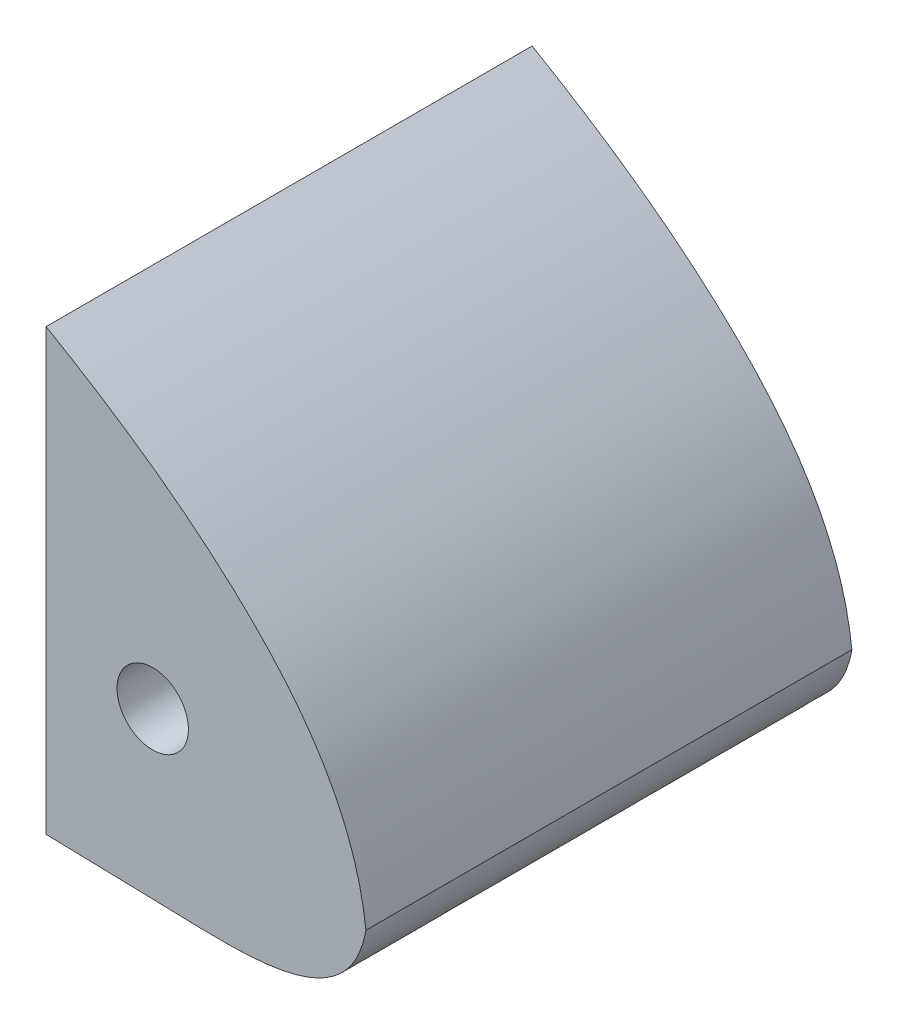
SolidWorks part; units mm, degrees
ref_plane "Front Plane" through (0, 0, 0) normal (0, 0, 1) x (1, 0, 0)
ref_plane "Top Plane" through (0, 0, 0) normal (0, 1, 0) x (1, 0, 0)
ref_plane "Right Plane" through (0, 0, 0) normal (1, 0, 0) x (0, 0, -1)
sketch "Sketch1" plane through (0, 0, 0) normal (0, 0, 1) x (1, 0, 0)
  line L0 (-66.007, 14.9523) -> (-66.007, -5.6347)
  circle A0 centre (63.517, -7.2283) radius 2.127
  circle A1 centre (-25.383, 13.0917) radius 2.127
  spline S0 degree 3 poles (76.217, -12.3083) (75.607, -6.7666) (69.7043, 1.1384) (56.4222, 10.2644) (36.9761, 19.3708) (8.7417, 24.8154) (-27.4552, 23.5667) (-52.3876, 18.1036) (-66.007, 14.9523) knots 0 0 0 0 0.086587 0.161737 0.268322 0.445157 0.638029 0.872371 0.872371 0.872371 0.872371
  spline S1 degree 3 poles (-66.007, -5.6347) (-44.594, -5.5392) (-13.013, -6.7241) (26.1367, -12.7509) (48.7653, -16.9008) (64.6834, -16.9691) (75.2906, -17.5225) (76.217, -12.3083) knots 0.133251 0.133251 0.133251 0.133251 0.51733 0.696667 0.84941 0.91952 1 1 1 1
extrude "Boss-Extrude1" add sketch "Sketch1" along normal blind 28.956
sketch "Sketch2" plane through (0, 0, 28.956) normal (0, 0, 1) x (1, 0, 0)
  line L0 (-66.007, 14.9523) -> (-66.007, -5.6347) construction
  line L1 (-77.1256, 30.6925) -> (57.167, 30.6925)
  line L2 (-77.1256, 30.6925) -> (-77.1256, -22.6703)
  line L3 (-77.1256, -22.6703) -> (57.167, -22.6703)
  line L4 (57.167, 30.6925) -> (57.167, -22.6703)
  dimension "D1" = 11.1187
  dimension "D2" = 19.05
extrude "Cut-Extrude1" cut sketch "Sketch2" against normal blind 28.956
